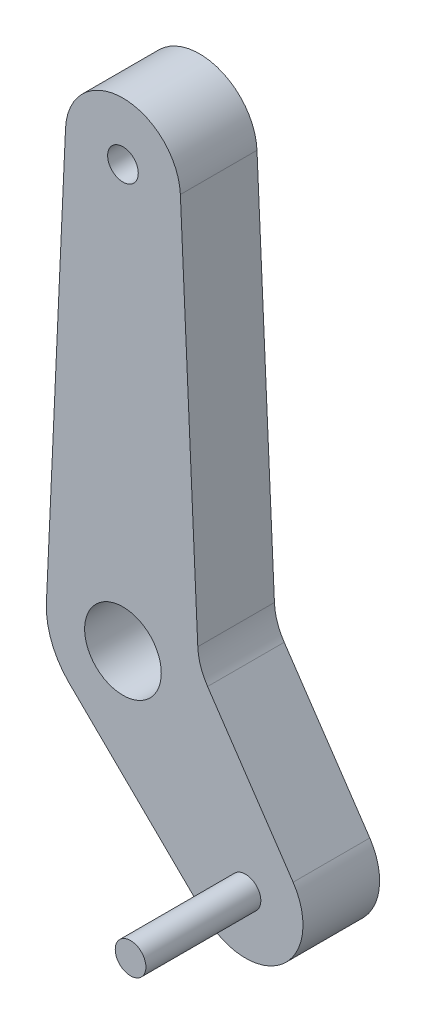
SolidWorks part; units mm, degrees
ref_plane "前视基准面" through (0, 0, 0) normal (0, 0, 1) x (1, 0, 0)
ref_plane "上视基准面" through (0, 0, 0) normal (0, 1, 0) x (1, 0, 0)
ref_plane "右视基准面" through (0, 0, 0) normal (1, 0, 0) x (0, 0, -1)
other "Configuration Table"
sketch "草图1" plane through (0, 0, 0) normal (0, 0, 1) x (1, 0, 0)
  line L0 (0, 0) -> (31.9854, -38.4309) construction
  line L1 (-14.9845, 110.6818) -> (-19.9793, 0.9091)
  line L2 (14.9845, 110.6818) -> (19.5318, 10.7454)
  line L3 (-14.0159, -14.2673) -> (21.4734, -49.1314)
  line L4 (44.4164, -30.0363) -> (22.0852, 3.0326)
  arc A0 (-19.9793, 0.9091) -> (-14.0159, -14.2673) centre (0, 0) ccw
  arc A1 (14.9845, 110.6818) -> (-14.9845, 110.6818) centre (0, 110) ccw
  arc A2 (21.4734, -49.1314) -> (44.4164, -30.0363) centre (31.9854, -38.4309) ccw
  arc A3 (22.0852, 3.0326) -> (19.5318, 10.7454) centre (34.5163, 11.4272) cw
  circle A4 centre (0, 0) radius 10
  circle A5 centre (0, 110) radius 4
  dimension "D1" = 15
extrude "凸台-拉伸1" add sketch "草图1" along normal blind 20
sketch "草图3" plane through (0, 0, 20) normal (0, 0, 1) x (1, 0, 0)
  circle A0 centre (31.9854, -38.4309) radius 4
extrude "凸台-拉伸2" add sketch "草图3" along normal blind 30
